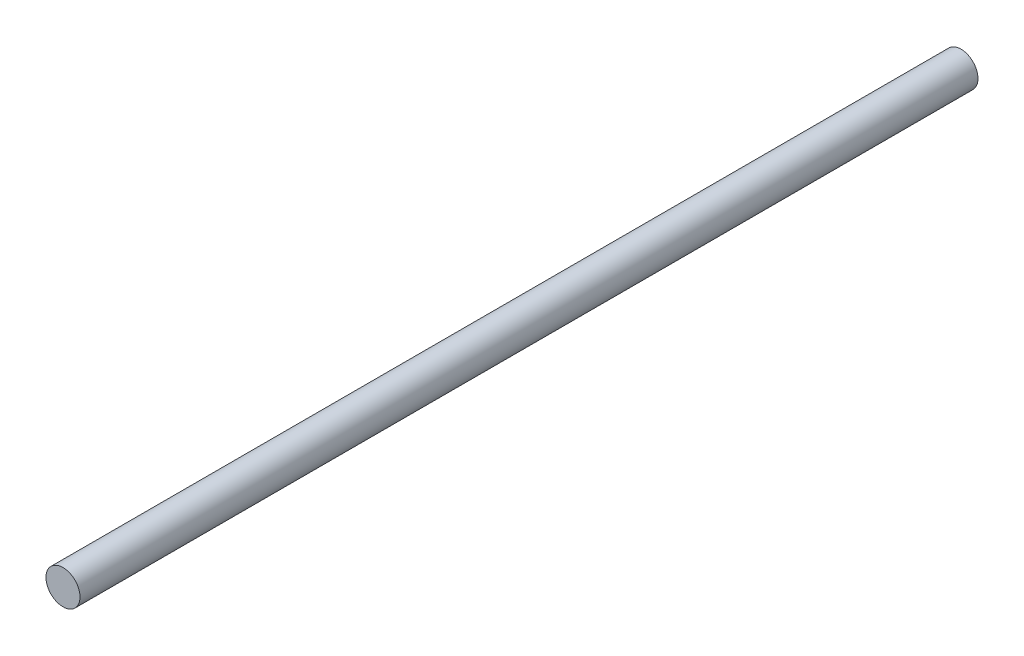
SolidWorks part; units mm, degrees
ref_plane "Front Plane" through (0, 0, 0) normal (0, 0, 1) x (1, 0, 0)
ref_plane "Top Plane" through (0, 0, 0) normal (0, 1, 0) x (1, 0, 0)
ref_plane "Right Plane" through (0, 0, 0) normal (1, 0, 0) x (0, 0, -1)
sketch "Sketch1" plane through (0, 0, 0) normal (0, 0, 1) x (1, 0, 0)
  circle A0 centre (0, 0) radius 11
extrude "CrossbarRod" add sketch "Sketch1" along normal blind 580
